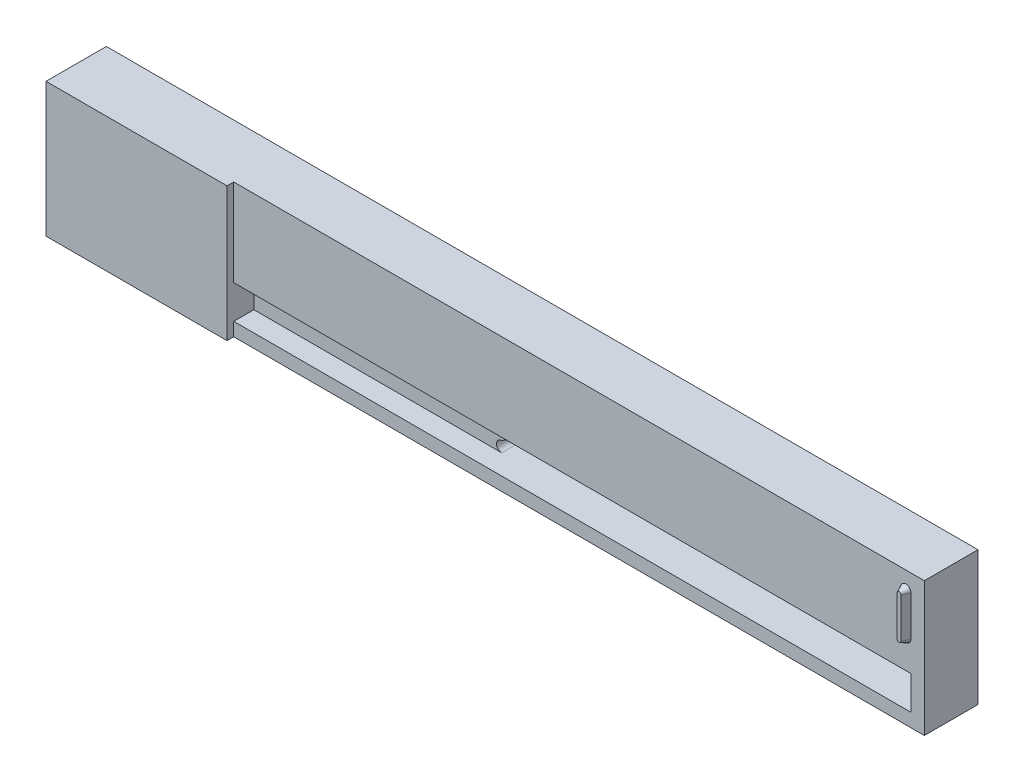
SolidWorks part; units mm, degrees
material "Plain Carbon Steel"
ref_plane "Front Plane" through (0, 0, 0) normal (0, 0, 1) x (1, 0, 0)
ref_plane "Top Plane" through (0, 0, 0) normal (0, 1, 0) x (1, 0, 0)
ref_plane "Right Plane" through (0, 0, 0) normal (1, 0, 0) x (0, 0, -1)
sketch "Sketch1" plane through (0, 0, 0) normal (0, 0, 1) x (1, 0, 0)
  line L1 (-65, -10) -> (65, -10)
  line L2 (-65, -10) -> (-65, 10)
  line L3 (-65, 10) -> (65, 10)
  line L4 (65, -10) -> (65, 10)
  line L5 (-65, -10) -> (65, 10) construction
  line L6 (-65, 10) -> (65, -10) construction
  point P0 (0, 0)
  dimension "D1" = 130
  dimension "D2" = 20
extrude "Boss-Extrude1" add sketch "Sketch1" along normal blind 8
sketch "Sketch2" plane through (-65, 0, 0) normal (-1, 0, 0) x (0, 0, 1)
  line L0 (8, 10) -> (0, 10) construction
  line L1 (1.6, -6.3) -> (4.6, -6.3)
  line L2 (1.6, -6.3) -> (1.6, 7.2)
  line L3 (1.6, 7.2) -> (4.6, 7.2)
  line L4 (4.6, -6.3) -> (4.6, 7.2)
  line L5 (1.6, -6.3) -> (4.6, 7.2) construction
  line L6 (1.6, 7.2) -> (4.6, -6.3) construction
  line L7 (0, 10) -> (0, -10) construction
  point P0 (3.1, 0.45)
  dimension "D1" = 13.5
  dimension "D2" = 3
  dimension "D3" = 2.8
  dimension "D4" = 1.6
extrude "Cut-Extrude1" cut sketch "Sketch2" against normal blind 7
sketch "Sketch3" plane through (0, 0, 8) normal (0, 0, 1) x (1, 0, 0)
  line L0 (65, 10) -> (-65, 10) construction
  line L1 (-65, 10) -> (-38, 10)
  line L2 (-65, 10) -> (-65, -10)
  line L3 (-65, -10) -> (-38, -10)
  line L4 (-38, 10) -> (-38, -10)
  line L5 (-65, 10) -> (-38, -10) construction
  line L6 (-65, -10) -> (-38, 10) construction
  line L7 (-65, 10) -> (-65, -10) construction
  point P0 (-51.5, 0)
  point P5 (-51.5, 10)
  dimension "D1" = 20
  dimension "D2" = 0
  dimension "D3" = 27
  dimension "D4" = 0
extrude "Boss-Extrude2" add sketch "Sketch3" along normal blind 1
sketch "Sketch4" plane through (0, 0, 0) normal (0, 0, -1) x (-1, 0, 0)
  line L0 (65, -10) -> (-65, -10) construction
  line L1 (-65, -10) -> (-65, 10) construction
  line L2 (-4, -9) -> (7, -9)
  line L3 (-64, -2) -> (-4, -2)
  line L4 (-64, -2) -> (-64, -9)
  line L5 (-64, -9) -> (-4, -9)
  line L6 (-4, -2) -> (-4, -9)
  line L7 (-63, -3) -> (-5, -3)
  line L8 (-63, -3) -> (-63, -8)
  line L9 (-63, -8) -> (-5, -8)
  line L10 (-5, -3) -> (-5, -8)
  line L11 (7, -9) -> (-4, -2)
  line L12 (-5, -8) -> (0, -8)
  line L13 (-5, -3) -> (0, -6.3697)
  circle A0 centre (-46, 4) radius 3.15
  arc A1 (0, -6.3697) -> (0, -8) centre (-0.8151, -7.1849) cw
  point P2 (-64, -5.5)
  dimension "D1" = 14
  dimension "D2" = 19
  dimension "D3" = 7
  dimension "D4" = 60
  dimension "D5" = 1
  dimension "D6" = 1
  dimension "D7" = 58
  dimension "D8" = 5
  dimension "D9" = 2
  dimension "D10" = 2
  dimension "D11" = 11
extrude "Cut-Extrude3" cut sketch "Sketch4" against normal blind 2 contours L3 L11 L2 L5 L4
sketch "Sketch6" plane through (0, 0, 2) normal (0, 0, -1) x (-1, 0, 0)
  line L0 (-65, -10) -> (-65, 10) construction
  line L1 (-63, -3) -> (-4, -3)
  line L2 (-63, -3) -> (-63, -8)
  line L3 (-63, -8) -> (-4, -8)
  line L4 (-4, -3) -> (-4, -8)
  line L5 (65, -10) -> (-65, -10) construction
  line L6 (-4, -8) -> (1.0291, -8)
  line L7 (-4, -3) -> (1.0291, -6.4273)
  arc A0 (1.0291, -6.4273) -> (1.0291, -8) centre (1.0291, -7.2136) cw
  point P4 (-63, -5.5)
  dimension "D1" = 59
  dimension "D2" = 2
  dimension "D3" = 5
  dimension "D4" = 2
extrude "Cut-Extrude4" cut sketch "Sketch6" against normal blind 7 contours L1 L7 A0 L6 L3 L2
sketch "Sketch7" plane through (0, 0, 0) normal (0, 0, -1) x (-1, 0, 0)
  line L0 (-65, 10) -> (65, 10) construction
  line L1 (-65, -10) -> (-65, 10) construction
  circle A0 centre (-46, 4) radius 3.15
  dimension "D1" = 6
  dimension "D2" = 19
extrude "Cut-Extrude5" cut sketch "Sketch7" against normal blind 3
sketch "Sketch8" plane through (0, 0, 3) normal (0, 0, -1) x (-1, 0, 0)
  line L0 (-46, 4) -> (-46, 6)
  line L1 (-46, 4) -> (-44.5858, 5.4142)
  arc A0 (-46, 6) -> (-44.5858, 5.4142) centre (-45.2929, 5.7071) cw
  dimension "D1" = 2
  dimension "D2" = 2
extrude "Boss-Extrude3" add sketch "Sketch8" along normal blind 1.5
pattern_circular "CirPattern1" count 8 over 360 about axis through (46, 4, 0) along (0, 0, 1) of "Boss-Extrude3"
sketch "Sketch9" plane through (0, 0, 1.5) normal (0, 0, -1) x (-1, 0, 0)
  circle A0 centre (-46, 4) radius 1
  circle A1 centre (-46, 4) radius 3.15 construction
  dimension "D1" = 0
extrude "Cut-Extrude6" cut sketch "Sketch9" against normal blind 1 draft 25
sketch "Sketch10" plane through (0, 0, 0) normal (0, 0, -1) x (-1, 0, 0)
  line L0 (-65, 10) -> (65, 10) construction
  circle A0 centre (-54.3465, 4) radius 0.5
  dimension "D1" = 6
  dimension "D2" = 1
extrude "Cut-Extrude7" cut sketch "Sketch10" against normal blind 3
sketch "Sketch11" plane through (0, 0, 8) normal (0, 0, 1) x (1, 0, 0)
  line L0 (-38, -10) -> (-38, 10) construction
  line L1 (63, -8) -> (-38, -8)
  line L2 (63, -8) -> (63, -3)
  line L3 (63, -3) -> (-38, -3)
  line L4 (-38, -8) -> (-38, -3)
extrude "Cut-Extrude8" cut sketch "Sketch11" against normal blind 3
sketch "Sketch13" plane through (-58, 0, 0) normal (-1, 0, 0) x (0, 0, 1)
  line L0 (2.3941, -5.1963) -> (2.3941, -4.1963)
  line L1 (2.3941, -5.1963) -> (3.2965, -5.1963)
  line L2 (2.3941, -4.1963) -> (3.2965, -4.1963)
  arc A0 (3.2965, -5.1963) -> (3.2965, -4.1963) centre (3.2965, -4.6963) ccw
  dimension "D1" = 1
extrude "Boss-Extrude5" add sketch "Sketch13" along normal blind 5
pattern_linear "LPattern2" count 5 spacing 1 along (0, 1, 0) of "Boss-Extrude5"
sketch "Sketch15" plane through (-58, 0, 0) normal (-1, 0, 0) x (0, 0, 1)
  line L0 (2.3941, 2.5504) -> (2.3941, 3.5504)
  line L1 (2.3941, 2.5504) -> (3.3941, 2.5504)
  line L2 (2.3941, 3.5504) -> (3.3941, 3.5504)
  arc A0 (3.3941, 2.5504) -> (3.3941, 3.5504) centre (3.3941, 3.0504) ccw
  dimension "D1" = 1
  dimension "D2" = 1
extrude "Boss-Extrude6" add sketch "Sketch15" along normal blind 5
pattern_linear "LPattern3" count 3 spacing 1 along (0, 1, 0) of "Boss-Extrude6"
sketch "Sketch16" plane through (0, 0, 8) normal (0, 0, 1) x (1, 0, 0)
  line L0 (63, 1.4377) -> (63, 7.4377)
  line L1 (61.4871, 1.4377) -> (61.4871, 7.4377)
  arc A0 (63, 1.4377) -> (61.4871, 1.4377) centre (62.2436, 1.4377) cw
  arc A1 (63, 7.4377) -> (61.4871, 7.4377) centre (62.2436, 7.4377) ccw
  dimension "D1" = 6
extrude "Boss-Extrude7" add sketch "Sketch16" along normal blind 1 draft 25
sketch "Sketch18" plane through (0, 0, 0) normal (0, 0, -1) x (-1, 0, 0)
  text T0 "intel" font "Century Gothic" height in points 24
extrude "Cut-Extrude10" cut sketch "Sketch18" against normal blind 1
sketch "Sketch17" [suppressed] plane through (0, 0, 0) normal (0, 0, -1) x (-1, 0, 0)
  text T0 "intel" font "Century Gothic" height in points 18
extrude "Cut-Extrude9" [suppressed] cut sketch "Sketch17" against normal blind 1
sketch "Sketch12" plane through (-58, 0, 0) normal (-1, 0, 0) x (0, 0, 1)
  line L0 (2.574, -5.1586) -> (2.574, -0.1586)
  line L1 (2.574, 2.2) -> (2.574, 6.2)
  line L2 (4.6, 7.2) -> (1.6, 7.2) construction
  line L3 (2.574, -5.1586) -> (3.5817, -5.1586)
  line L4 (2.574, -0.1586) -> (3.5817, -0.1586)
  line L5 (2.574, -4.1586) -> (3.5817, -4.1586)
  line L6 (2.574, -3.1586) -> (3.5817, -3.1586)
  line L7 (2.574, -1.1586) -> (3.5817, -1.1586)
  line L8 (2.574, -2.1586) -> (3.5817, -2.1586)
  line L9 (2.574, 2.2) -> (3.5817, 2.2)
  line L10 (2.574, 6.2) -> (3.5817, 6.2)
  line L11 (2.574, 3.2) -> (3.5817, 3.2)
  line L12 (2.574, 4.2) -> (3.5817, 4.2)
  line L13 (2.574, 5.2) -> (3.5817, 5.2)
  arc A0 (3.5817, 2.2) -> (3.5817, 3.2) centre (3.5817, 2.7) ccw
  arc A1 (3.5817, -5.1586) -> (3.5817, -4.1586) centre (3.5817, -4.6586) ccw
  arc A2 (3.5817, -4.1586) -> (3.5817, -3.1586) centre (3.5817, -3.6586) ccw
  arc A3 (3.5817, -3.1586) -> (3.5817, -2.1586) centre (3.5817, -2.6586) ccw
  arc A4 (3.5817, -1.1586) -> (3.5817, -2.1586) centre (3.5817, -1.6586) cw
  arc A5 (3.5817, -1.1586) -> (3.5817, -0.1586) centre (3.5817, -0.6586) ccw
  arc A6 (3.5817, 3.2) -> (3.5817, 4.2) centre (3.5817, 3.7) ccw
  arc A7 (3.5817, 4.2) -> (3.5817, 5.2) centre (3.5817, 4.7) ccw
  arc A8 (3.5817, 5.2) -> (3.5817, 6.2) centre (3.5817, 5.7) ccw
  dimension "D1" = 5
  dimension "D2" = 4
  dimension "D3" = 1
  dimension "D4" = 1
  dimension "D5" = 1
  dimension "D6" = 1
  dimension "D7" = 1
  dimension "D8" = 1
  dimension "D9" = 1
  dimension "D10" = 1
